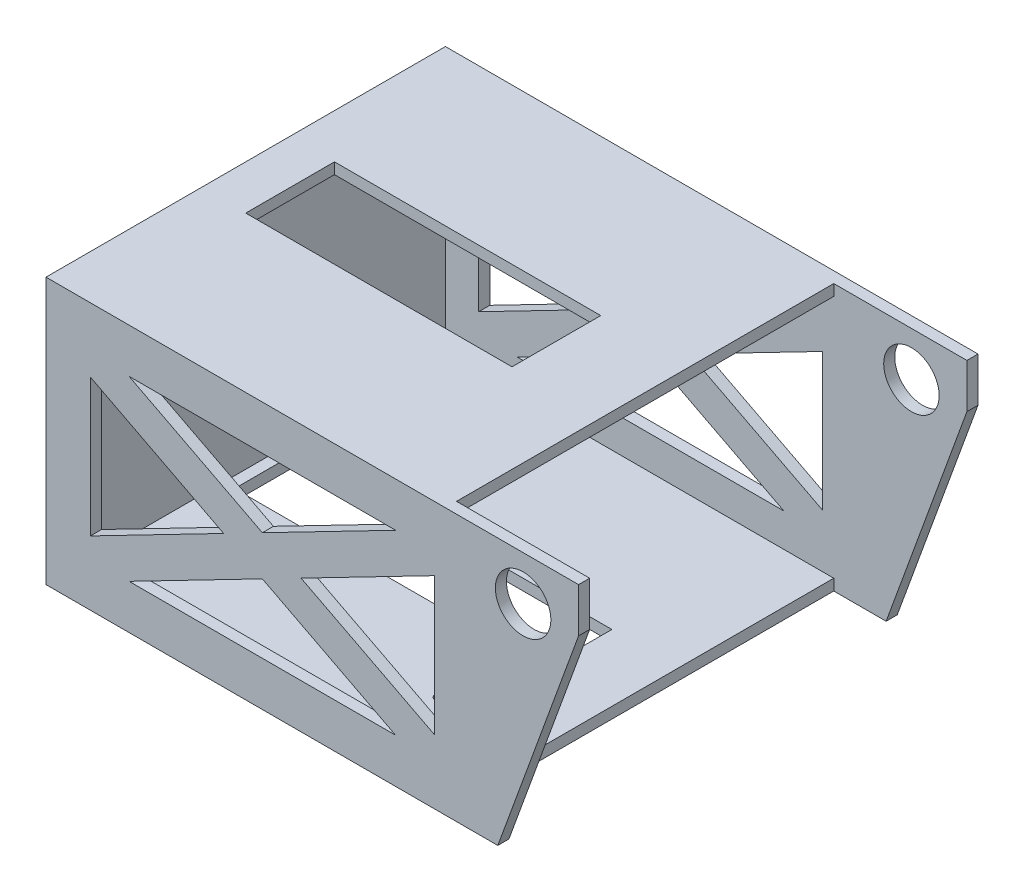
SolidWorks part; units mm, degrees
ref_plane "Front Plane" through (0, 0, 0) normal (0, 0, 1) x (1, 0, 0)
ref_plane "Top Plane" through (0, 0, 0) normal (0, 1, 0) x (1, 0, 0)
ref_plane "Right Plane" through (0, 0, 0) normal (1, 0, 0) x (0, 0, -1)
sketch "Sketch1" plane through (0, 0, 0) normal (0, 1, 0) x (1, 0, 0)
  line L1 (-97.1195, 44.7734) -> (55.2805, 44.7734)
  line L2 (-97.1195, 44.7734) -> (-97.1195, -69.5266)
  line L3 (-97.1195, -69.5266) -> (55.2805, -69.5266)
  line L4 (55.2805, 44.7734) -> (55.2805, -69.5266)
  dimension "D1" = 152.4
  dimension "D2" = 114.3
extrude "Boss-Extrude1" add sketch "Sketch1" along normal blind 76.2
sketch "Sketch3" plane through (0, 0, 0) normal (0, 0, 1) x (1, 0, 0)
  line L0 (55.2805, 76.2) -> (55.2805, 63.5)
  line L1 (55.2805, 76.2) -> (55.2805, 0) construction
  line L2 (55.2805, 63.5) -> (32.1684, 0)
  line L3 (-97.1195, 0) -> (55.2805, 0) construction
  line L4 (32.1684, 0) -> (55.2805, 0)
  line L5 (55.2805, 0) -> (55.2805, 63.5)
  dimension "D1" = 12.7
  dimension "D2" = 20
extrude "Cut-Extrude1" cut sketch "Sketch3" against normal through all and the other way through all contours L2 L4 L5
sketch "Sketch4" plane through (0, 0, 0) normal (0, 0, 1) x (1, 0, 0)
  line L1 (-93.9445, 3.175) -> (28.9934, 3.175)
  line L2 (-93.9445, 3.175) -> (-93.9445, 73.025)
  line L3 (-93.9445, 73.025) -> (28.9934, 73.025)
  line L4 (28.9934, 3.175) -> (28.9934, 73.025)
  line L5 (-97.1195, 0) -> (32.1684, 0) construction
  line L6 (-97.1195, 76.2) -> (-97.1195, 0) construction
  line L8 (-97.1195, 76.2) -> (55.2805, 76.2) construction
  dimension "D1" = 3.175
  dimension "D2" = 3.175
  dimension "D3" = 3.175
  dimension "D4" = 3.175
sketch "Sketch5" plane through (0, 0, 0) normal (0, 1, 0) x (1, 0, 0)
  line L1 (17.1805, 41.5984) -> (55.2805, 41.5984)
  line L2 (17.1805, 41.5984) -> (17.1805, -66.3516)
  line L3 (17.1805, -66.3516) -> (55.2805, -66.3516)
  line L4 (55.2805, 41.5984) -> (55.2805, -66.3516)
  line L5 (55.2805, 44.7734) -> (-97.1195, 44.7734) construction
  line L6 (-97.1195, -69.5266) -> (55.2805, -69.5266) construction
  line L7 (55.2805, -69.5266) -> (55.2805, 44.7734) construction
  dimension "D1" = 3.175
  dimension "D2" = 3.175
  dimension "D3" = 0
  dimension "D4" = 38.1
extrude "Cut-Extrude4" cut sketch "Sketch5" along normal through all contours L3 L4 L1 L2
sketch "Sketch6" plane through (0, 0, 69.5266) normal (0, 0, 1) x (1, 0, 0)
  line L0 (55.2805, 76.2) -> (55.2805, 63.5) construction
  line L1 (-97.1195, 76.2) -> (55.2805, 76.2) construction
  circle A0 centre (39.4055, 63.5) radius 7.9375
  dimension "D1" = 15.875
  dimension "D2" = 15.875
  dimension "D3" = 12.7
extrude "Cut-Extrude5" cut sketch "Sketch6" against normal through all both and the other way through all
sketch "Sketch8" plane through (-97.1195, 0, 0) normal (-1, 0, 0) x (0, 0, 1)
  line L0 (-44.7734, 76.2) -> (-44.7734, 0) construction
  line L1 (-41.5984, 73.025) -> (66.3516, 73.025)
  line L2 (-41.5984, 73.025) -> (-41.5984, 3.175)
  line L3 (-41.5984, 3.175) -> (66.3516, 3.175)
  line L4 (66.3516, 73.025) -> (66.3516, 3.175)
  line L5 (69.5266, 76.2) -> (69.5266, 0) construction
  line L6 (-44.7734, 76.2) -> (69.5266, 76.2) construction
  line L7 (-44.7734, 0) -> (69.5266, 0) construction
  dimension "D1" = 3.175
  dimension "D2" = 3.175
  dimension "D3" = 3.175
  dimension "D4" = 3.175
extrude "Cut-Extrude6" cut sketch "Sketch8" along normal offset from surface (111.125 mm away) 3.175 from surface at -114.3 up to face at (-97.1195, 38.1, 12.3766) starting at face at (17.1805, 38.1, 12.3766)
sketch "Sketch9" plane through (0, 0, 0) normal (0, -1, 0) x (1, 0, 0)
  line L0 (17.1805, -41.5984) -> (17.1805, 66.3516) construction
  line L1 (-97.1195, 69.5266) -> (32.1684, 69.5266) construction
  circle A0 centre (4.4805, 44.1266) radius 1.5875
  circle A1 centre (-9.4895, 44.1266) radius 1.5875
  dimension "D1" = 3.175
  dimension "D2" = 3.175
  dimension "D3" = 0
  dimension "D4" = 12.7
  dimension "D5" = 13.97
  dimension "D6" = 25.4
extrude "Cut-Extrude7" cut sketch "Sketch9" against normal blind 3.175
sketch "Sketch10" plane through (0, 0, 0) normal (0, -1, 0) x (1, 0, 0)
  line L0 (-97.1195, 69.5266) -> (32.1684, 69.5266) construction
  line L1 (-90.7695, 21.9016) -> (-1.8695, 21.9016)
  line L2 (-90.7695, 21.9016) -> (-90.7695, 2.8516)
  line L3 (-90.7695, 2.8516) -> (-1.8695, 2.8516)
  line L4 (-1.8695, 21.9016) -> (-1.8695, 2.8516)
  line L5 (-90.7695, 21.9016) -> (-1.8695, 2.8516) construction
  line L6 (-90.7695, 2.8516) -> (-1.8695, 21.9016) construction
  line L7 (-97.1195, -44.7734) -> (-97.1195, 69.5266) construction
  point P0 (-46.3195, 12.3766)
  dimension "D1" = 57.15
  dimension "D2" = 50.8
  dimension "D3" = 88.9
  dimension "D4" = 19.05
extrude "Cut-Extrude8" cut sketch "Sketch10" against normal blind 5.715
sketch "Sketch12" plane through (0, 0, 69.5266) normal (0, 0, 1) x (1, 0, 0)
  line L0 (-97.1195, 76.2) -> (-97.1195, 0) construction
  line L1 (-73.3433, 63.5) -> (2.9293, 63.5)
  line L2 (-84.4195, 57.7833) -> (-84.4195, 18.4167)
  line L3 (-73.3433, 12.7) -> (2.9293, 12.7)
  line L4 (14.0055, 57.7833) -> (14.0055, 18.4167)
  line L5 (-97.1195, 76.2) -> (55.2805, 76.2) construction
  line L6 (-97.1195, 0) -> (32.1684, 0) construction
  line L7 (-35.207, 43.8167) -> (-73.3433, 63.5)
  line L9 (-84.4195, 57.7833) -> (-46.2832, 38.1)
  line L10 (14.0055, 18.4167) -> (-24.1308, 38.1)
  line L11 (-84.4195, 18.4167) -> (-46.2832, 38.1)
  line L12 (14.0055, 57.7833) -> (-24.1308, 38.1)
  line L13 (-35.207, 43.8167) -> (2.9293, 63.5)
  line L15 (-35.207, 32.3833) -> (-73.3433, 12.7)
  line L17 (-35.207, 32.3833) -> (2.9293, 12.7)
  circle A0 centre (39.4055, 63.5) radius 7.9375 construction
  dimension "D1" = 12.7
  dimension "D2" = 12.7
  dimension "D3" = 12.7
  dimension "D4" = 25.4
extrude "Cut-Extrude9" cut sketch "Sketch12" against normal through all
sketch "Sketch13" plane through (0, 76.2, 0) normal (0, 1, 0) x (1, 0, 0)
  line L0 (-97.1195, 44.7734) -> (-97.1195, -69.5266) construction
  line L1 (-84.4195, 0.3234) -> (-8.2195, 0.3234)
  line L2 (-84.4195, 0.3234) -> (-84.4195, -25.0766)
  line L3 (-84.4195, -25.0766) -> (-8.2195, -25.0766)
  line L4 (-8.2195, 0.3234) -> (-8.2195, -25.0766)
  line L5 (55.2805, 44.7734) -> (-97.1195, 44.7734) construction
  dimension "D1" = 25.4
  dimension "D2" = 76.2
  dimension "D3" = 12.7
  dimension "D4" = 44.45
extrude "Cut-Extrude10" cut sketch "Sketch13" against normal blind 5.715
